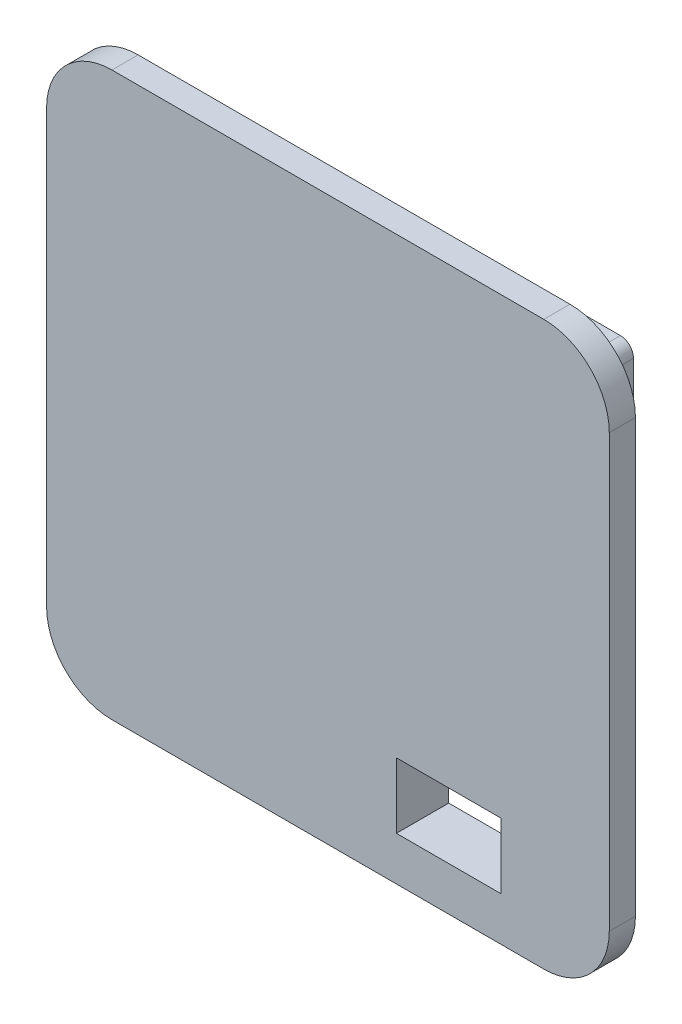
SolidWorks part; units mm, degrees
ref_plane "Front Plane" through (0, 0, 0) normal (1, 0, 0) x (0, 1, 0)
ref_plane "Top Plane" through (0, 0, 0) normal (0, 0, 1) x (0, 1, 0)
ref_plane "Right Plane" through (0, 0, 0) normal (0, 1, 0) x (-1, 0, 0)
sketch "Sketch1" plane through (0, 0, 0) normal (0, 0, 1) x (0, 1, 0)
  line L1 (21.5, -21.5) -> (-21.5, -21.5)
  line L2 (21.5, -21.5) -> (21.5, 21.5)
  line L3 (21.5, 21.5) -> (-21.5, 21.5)
  line L4 (-21.5, -21.5) -> (-21.5, 21.5)
  line L5 (21.5, -21.5) -> (-21.5, 21.5) construction
  line L6 (21.5, 21.5) -> (-21.5, -21.5) construction
  point P0 (0, 0)
  dimension "D1" = 43
  dimension "D2" = 43
extrude "Boss-Extrude1" add sketch "Sketch1" along normal blind 2
fillet "Fillet1" radius 5 4 edges at (21.5, -21.5, 1) (-21.5, -21.5, 1) (-21.5, 21.5, 1) (21.5, 21.5, 1)
sketch "Sketch2" plane through (0, 0, 2) normal (0, 0, 1) x (1, 0, 0)
  line L1 (13.2321, -18.1481) -> (5.2321, -18.1481)
  line L2 (13.2321, -18.1481) -> (13.2321, -13.1481)
  line L3 (13.2321, -13.1481) -> (5.2321, -13.1481)
  line L4 (5.2321, -18.1481) -> (5.2321, -13.1481)
  line L5 (13.2321, -18.1481) -> (5.2321, -13.1481) construction
  line L6 (13.2321, -13.1481) -> (5.2321, -18.1481) construction
  point P0 (9.2321, -15.6481)
  point P5 (9.2321, -15.6481)
  dimension "D1" = 8
  dimension "D2" = 5
extrude "Cut-Extrude1" cut sketch "Sketch2" against normal through all
sketch "Sketch3" plane through (0, 0, 0) normal (0, 0, -1) x (0, 1, 0)
  line L0 (19.35, -19.35) -> (19.35, 19.35)
  line L1 (19.5, -19.5) -> (-19.5, -19.5)
  line L2 (19.5, -19.5) -> (19.5, 19.5)
  line L3 (19.5, 19.5) -> (-19.5, 19.5)
  line L4 (-19.5, -19.5) -> (-19.5, 19.5)
  line L5 (19.5, -19.5) -> (-19.5, 19.5) construction
  line L6 (19.5, 19.5) -> (-19.5, -19.5) construction
  line L7 (19.35, 19.35) -> (-19.35, 19.35)
  line L8 (-19.35, -19.35) -> (-19.35, 19.35)
  line L9 (19.35, -19.35) -> (-19.35, -19.35)
  point P0 (0, 0)
  line M10 (-13.1481, 13.2321) -> (-13.1481, 5.2321)
  line M11 (-13.1481, 5.2321) -> (-18.1481, 5.2321)
  line M12 (-18.1481, 5.2321) -> (-18.1481, 13.2321)
  line M13 (-18.1481, 13.2321) -> (-13.1481, 13.2321)
  dimension "D1" = 39
  dimension "D2" = 39
  dimension "D3" = 0.15
extrude "Boss-Extrude2" add sketch "Sketch3" along normal blind 2 contours L9 L0 L7 L8 M13 M10 M11 M12
fillet "Fillet3" radius 1 4 edges at (-19.35, 19.35, -1) (19.35, 19.35, -1) (19.35, -19.35, -1) (-19.35, -19.35, -1)
